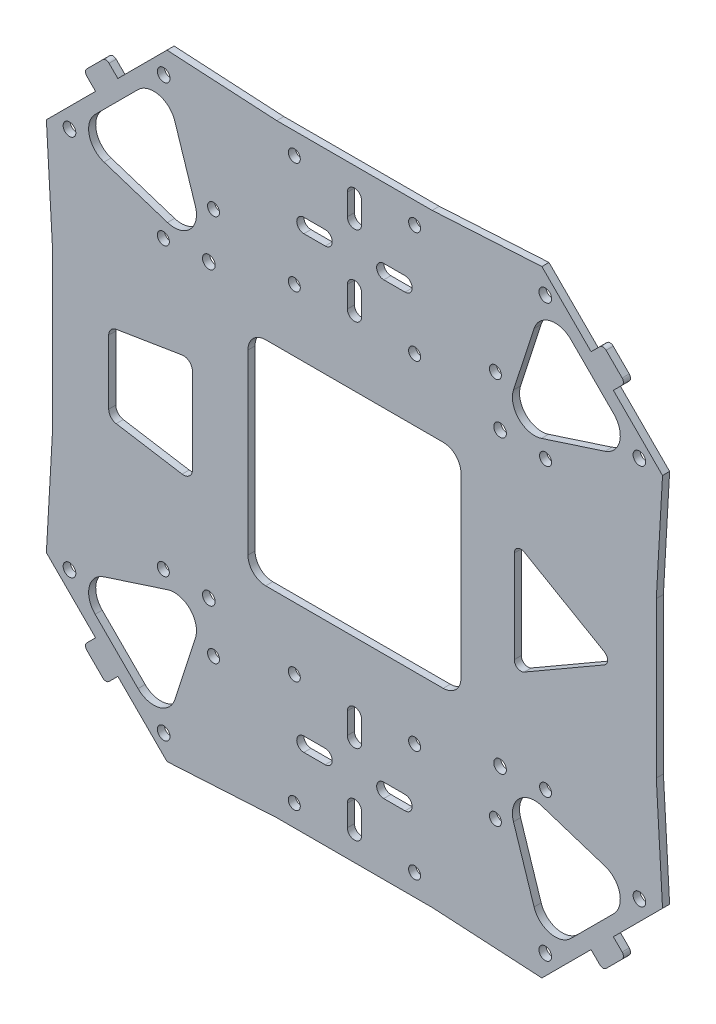
SolidWorks part; units mm, degrees
ref_plane "Front Plane" through (0, 0, 0) normal (0, 0, 1) x (1, 0, 0)
ref_plane "Top Plane" through (0, 0, 0) normal (0, 1, 0) x (1, 0, 0)
ref_plane "Right Plane" through (0, 0, 0) normal (1, 0, 0) x (0, 0, -1)
sketch "Sketch1" plane through (0, 0, 0) normal (0, 0, 1) x (1, 0, 0)
  line L16 (68, 0) -> (68, 17.5)
  line L17 (68, 0) -> (68, -17.5)
  line L21 (68, 17.5) -> (69.4, 42.225)
  line L23 (68, -17.5) -> (69.4, -42.225)
  line L24 (-68, 0) -> (-68, 17.5)
  line L25 (-68, 0) -> (-68, -17.5)
  line L30 (-68, 17.5) -> (-69.4, 42.225)
  line L31 (-68, -17.5) -> (-69.4, -42.225)
  line L32 (0, -68) -> (-17.5, -68)
  line L33 (0, -68) -> (17.5, -68)
  line L37 (42.225, -68) -> (42.225, -69.4) construction
  line L38 (-17.5, -68) -> (-42.225, -69.4)
  line L39 (17.5, -68) -> (42.225, -69.4)
  line L40 (0, 68) -> (-17.5, 68)
  line L41 (0, 68) -> (17.5, 68)
  line L46 (-17.5, 68) -> (-42.225, 69.4)
  line L47 (17.5, 68) -> (42.225, 69.4)
  line L48 (-69.4, 42.225) -> (-58.3227, 53.3023)
  line L49 (-53.3023, 58.3227) -> (-42.225, 69.4)
  line L50 (-58.4995, 58.4995) -> (-61.0097, 55.9893)
  line L51 (-58.4995, 58.4995) -> (-55.9893, 61.0097)
  line L52 (-61.0097, 55.9893) -> (-58.3227, 53.3023)
  line L53 (-55.9893, 61.0097) -> (-53.3023, 58.3227)
  line L54 (42.225, 69.4) -> (53.3023, 58.3227)
  line L55 (-69.4, -42.225) -> (-58.3227, -53.3023)
  line L56 (42.225, -69.4) -> (53.3023, -58.3227)
  line L57 (58.3227, -53.3023) -> (69.4, -42.225)
  line L58 (58.4995, 58.4995) -> (55.9893, 61.0097)
  line L59 (58.4995, 58.4995) -> (61.0097, 55.9893)
  line L60 (55.9893, 61.0097) -> (53.3023, 58.3227)
  line L61 (61.0097, 55.9893) -> (58.3227, 53.3023)
  line L64 (58.4995, -58.4995) -> (55.9893, -61.0097)
  line L65 (58.4995, -58.4995) -> (61.0097, -55.9893)
  line L66 (55.9893, -61.0097) -> (53.3023, -58.3227)
  line L67 (61.0097, -55.9893) -> (58.3227, -53.3023)
  line L68 (-53.3023, -58.3227) -> (-42.225, -69.4)
  line L69 (-58.4995, -58.4995) -> (-61.0097, -55.9893)
  line L70 (-58.4995, -58.4995) -> (-55.9893, -61.0097)
  line L71 (-61.0097, -55.9893) -> (-58.3227, -53.3023)
  line L72 (-55.9893, -61.0097) -> (-53.3023, -58.3227)
  line L75 (58.3227, 53.3023) -> (69.4, 42.225)
  point P0 (0, 0)
  point P6 (0, 0)
  dimension "D3" = 3.8
  dimension "D9" = 17.5
  dimension "D10" = 17.5
  dimension "D13" = 17.5
  dimension "D14" = 17.5
  dimension "D16" = 24.725
  dimension "D18" = 3.55
  dimension "D19" = 3.55
  dimension "D21" = 3.55
  dimension "D22" = 3.55
  dimension "D24" = 3.55
extrude "Boss-Extrude1" add sketch "Sketch1" along normal blind 1.6
ref_plane "Plane1" through (0, 0, 1.6) normal (0, 0, 1) x (1, 0, 0)
sketch "Sketch2" plane through (0, 0, 1.6) normal (0, 0, 1) x (1, 0, 0)
  line L0 (24, 0) -> (36, 0) construction
  line L1 (20, -24) -> (-20, -24)
  line L2 (24, -20) -> (24, 20)
  line L3 (20, 24) -> (-20, 24)
  line L4 (-24, -20) -> (-24, 20)
  line L5 (24, -24) -> (-24, 24) construction
  line L6 (24, 24) -> (-24, -24) construction
  line L7 (36, 0) -> (36, 10.4019)
  line L8 (36, 0) -> (36, -10.4019)
  line L9 (36, 0) -> (58.5167, 0) construction
  line L10 (38.25, 11.701) -> (56.2667, 1.299)
  line L11 (38.25, -11.701) -> (56.2667, -1.299)
  line L12 (-24, 0) -> (-36.5, 0) construction
  line L13 (-36.5, 0) -> (-36.5, 9.6475)
  line L14 (-36.5, 0) -> (-36.5, -9.6475)
  line L15 (-36.5, 0) -> (-55.36, 0) construction
  line L16 (-55.36, 0) -> (-55.36, 7.2247)
  line L17 (-55.36, 0) -> (-55.36, -7.2247)
  line L18 (-53.6818, 9.1986) -> (-38.8218, 11.6214)
  line L19 (-53.6818, -9.1986) -> (-38.8218, -11.6214)
  line L20 (0, 0) -> (0, 32.15) construction
  line L21 (0, 0) -> (0, -32.15) construction
  line L22 (0, 0) -> (-31.65, 0) construction
  line L23 (0, 0) -> (-31.65, 0) construction
  line L24 (-31.65, 0) -> (-31.65, 32.15) construction
  line L25 (-31.65, 0) -> (-31.65, -32.15) construction
  line L26 (0, 0) -> (31.65, 0) construction
  line L27 (31.65, 0) -> (31.65, 32.15) construction
  line L28 (31.65, 0) -> (31.65, -32.15) construction
  arc A0 (20, -24) -> (24, -20) centre (20, -20) ccw
  arc A1 (24, 20) -> (20, 24) centre (20, 20) ccw
  arc A2 (-20, -24) -> (-24, -20) centre (-20, -20) cw
  arc A3 (-24, 20) -> (-20, 24) centre (-20, 20) cw
  arc A4 (38.25, -11.701) -> (36, -10.4019) centre (37.5, -10.4019) cw
  arc A5 (36, 10.4019) -> (38.25, 11.701) centre (37.5, 10.4019) cw
  arc A6 (56.2667, -1.299) -> (56.2667, 1.299) centre (55.5167, 0) ccw
  arc A7 (-53.6818, -9.1986) -> (-55.36, -7.2247) centre (-53.36, -7.2247) cw
  arc A8 (-38.8218, -11.6214) -> (-36.5, -9.6475) centre (-38.5, -9.6475) ccw
  arc A9 (-36.5, 9.6475) -> (-38.8218, 11.6214) centre (-38.5, 9.6475) ccw
  arc A10 (-55.36, 7.2247) -> (-53.6818, 9.1986) centre (-53.36, 7.2247) cw
  point P0 (0, 0)
  point P25 (36, -13)
  point P28 (36, 13)
  point P41 (-55.36, -8.925)
  point P44 (-36.5, -12)
  point P47 (-36.5, 12)
  point P50 (-55.36, 8.925)
  dimension "D3" = 4
  dimension "D8" = 1.5
  dimension "D15" = 2
  dimension "D1" = 48
  dimension "D2" = 48
  dimension "D4" = 12
  dimension "D5" = 13
  dimension "D6" = 13
  dimension "D7" = 26
  dimension "D9" = 12.5
  dimension "D10" = 12
  dimension "D11" = 12
  dimension "D12" = 18.86
  dimension "D13" = 8.925
  dimension "D14" = 8.925
  dimension "D16" = 32.15
  dimension "D17" = 32.15
  dimension "D18" = 31.65
  dimension "D19" = 31.65
extrude "Cut-Extrude1" cut sketch "Sketch2" against normal through all
ref_plane "Plane2" through (0, 0, 1.6) normal (0, 0, 1) x (1, 0, 0)
sketch "Sketch3" plane through (0, 0, 1.6) normal (0, 0, 1) x (1, 0, 0)
  line L0 (0, 0) -> (-43.05, 0) construction
  line L1 (0, 0) -> (43.05, 0) construction
  line L3 (-43.05, 0) -> (-43.05, 32.275) construction
  line L4 (-43.05, 0) -> (-43.05, -32.275) construction
  line L5 (43.05, 0) -> (43.05, 32.275) construction
  line L6 (43.05, 0) -> (43.05, -32.275) construction
  circle A0 centre (-43.05, -32.275) radius 1.35
  circle A1 centre (-43.05, 32.275) radius 1.35
  circle A2 centre (43.05, 32.275) radius 1.35
  circle A3 centre (43.05, -32.275) radius 1.35
  dimension "D5" = 2.7
  dimension "D6" = 2.7
  dimension "D7" = 2.7
  dimension "D8" = 2.7
  dimension "D1" = 43.05
  dimension "D2" = 43.05
  dimension "D3" = 32.275
  dimension "D4" = 32.275
extrude "Cut-Extrude2" cut sketch "Sketch3" against normal blind 10
ref_plane "Plane3" through (0, 0, 1.6) normal (0, 0, 1) x (1, 0, 0)
sketch "Sketch4" plane through (0, 0, 1.6) normal (0, 0, 1) x (1, 0, 0)
  line L0 (0, 0) -> (31.75, 0) construction
  line L1 (0, 0) -> (-31.75, 0) construction
  line L2 (-31.75, 0) -> (-31.75, 42.25) construction
  line L3 (-31.75, 0) -> (-31.75, -42.25) construction
  line L4 (31.75, 0) -> (31.75, 43.6) construction
  line L5 (31.75, 0) -> (31.75, -43.6) construction
  line L6 (0, 0) -> (0, 38.05) construction
  line L7 (0, 0) -> (0, -38.05) construction
  line L8 (-13.55, -63.15) -> (13.55, -38.05) construction
  line L9 (0, -50.6) -> (0, -55.6) construction
  line L10 (0, -38.05) -> (13.55, -38.05) construction
  line L11 (0, -38.05) -> (-13.55, -38.05) construction
  line L12 (-6.6, -52.2) -> (-11.4, -52.2)
  line L13 (-1.6, -57.2) -> (-1.6, -62)
  line L14 (-13.55, -38.05) -> (-13.55, -63.15) construction
  line L15 (13.55, -38.05) -> (13.55, -63.15) construction
  line L16 (1.6, -57.2) -> (1.6, -62)
  line L17 (-6.6, -49) -> (-11.4, -49)
  line L18 (-1.6, -44) -> (-1.6, -39.2)
  line L39 (1.6, -44) -> (1.6, -39.2)
  line L40 (6.6, -49) -> (11.4, -49)
  line L41 (6.6, -52.2) -> (11.4, -52.2)
  line L42 (0, 38.05) -> (-13.55, 38.05) construction
  line L43 (0, 38.05) -> (13.55, 38.05) construction
  line L44 (-13.55, 38.05) -> (-13.55, 63.15) construction
  line L45 (13.55, 38.05) -> (13.55, 63.15) construction
  line L46 (-13.55, 63.15) -> (13.55, 63.15) construction
  line L47 (13.55, 63.15) -> (-13.55, 38.05) construction
  line L48 (0, 50.6) -> (0, 55.6) construction
  line L49 (6.6, 49) -> (11.4, 49)
  line L50 (-1.6, 57.2) -> (-1.6, 62)
  line L51 (1.6, 57.2) -> (1.6, 62)
  line L52 (6.6, 52.2) -> (11.4, 52.2)
  line L53 (-1.6, 44) -> (-1.6, 39.2)
  line L54 (1.6, 44) -> (1.6, 39.2)
  line L55 (-6.6, 52.2) -> (-11.4, 52.2)
  line L56 (-6.6, 49) -> (-11.4, 49)
  circle A0 centre (-31.75, -43.6) radius 1.35
  circle A1 centre (31.75, -43.6) radius 1.35
  circle A2 centre (31.75, 43.6) radius 1.35
  circle A3 centre (-31.75, 43.6) radius 1.35
  circle A4 centre (13.55, -38.05) radius 1.35
  circle A5 centre (-13.55, -38.05) radius 1.35
  circle A6 centre (13.55, 38.05) radius 1.35
  circle A7 centre (-13.55, 38.05) radius 1.35
  circle A8 centre (-13.55, 63.15) radius 1.35
  circle A10 centre (-13.55, -63.15) radius 1.35
  circle A11 centre (13.55, -63.15) radius 1.35
  arc A21 (1.6, -57.2) -> (-1.6, -57.2) centre (0, -57.2) ccw
  arc A22 (-1.6, -62) -> (1.6, -62) centre (0, -62) ccw
  arc A23 (-6.6, -52.2) -> (-6.6, -49) centre (-6.6, -50.6) ccw
  arc A24 (-11.4, -49) -> (-11.4, -52.2) centre (-11.4, -50.6) ccw
  arc A25 (-1.6, -44) -> (1.6, -44) centre (0, -44) ccw
  arc A26 (1.6, -39.2) -> (-1.6, -39.2) centre (0, -39.2) ccw
  arc A27 (6.6, -49) -> (6.6, -52.2) centre (6.6, -50.6) ccw
  arc A28 (11.4, -52.2) -> (11.4, -49) centre (11.4, -50.6) ccw
  circle A29 centre (13.55, 63.15) radius 1.35
  arc A30 (-1.6, 57.2) -> (1.6, 57.2) centre (0, 57.2) ccw
  arc A31 (1.6, 62) -> (-1.6, 62) centre (0, 62) ccw
  arc A32 (11.4, 49) -> (11.4, 52.2) centre (11.4, 50.6) ccw
  arc A33 (6.6, 52.2) -> (6.6, 49) centre (6.6, 50.6) ccw
  arc A34 (-1.6, 39.2) -> (1.6, 39.2) centre (0, 39.2) ccw
  arc A35 (1.6, 44) -> (-1.6, 44) centre (0, 44) ccw
  arc A36 (-11.4, 52.2) -> (-11.4, 49) centre (-11.4, 50.6) ccw
  arc A37 (-6.6, 49) -> (-6.6, 52.2) centre (-6.6, 50.6) ccw
  point P64 (0, 50.6)
  point P87 (0, -50.6)
  point P89 (0, 50.6)
  dimension "D5" = 2.7
  dimension "D6" = 2.7
  dimension "D7" = 2.7
  dimension "D8" = 2.7
  dimension "D13" = 2.7
  dimension "D14" = 2.7
  dimension "D15" = 2.7
  dimension "D16" = 2.7
  dimension "D19" = 2.7
  dimension "D20" = 2.7
  dimension "D21" = 2.7
  dimension "D22" = 2.7
  dimension "D1" = 31.75
  dimension "D2" = 31.75
  dimension "D3" = 43.6
  dimension "D4" = 43.6
  dimension "D9" = 5
  dimension "D10" = 38.05
  dimension "D11" = 1.6
  dimension "D12" = 4.8
  dimension "D17" = 25.1
  dimension "D18" = 25.1
  dimension "D23" = 4
  dimension "D24" = 38.05
  dimension "D25" = 13.55
  dimension "D26" = 13.55
  dimension "D27" = 5
  dimension "D28" = 1.6
  dimension "D29" = 4.8
  dimension "D30" = 4
extrude "Cut-Extrude3" cut sketch "Sketch4" against normal blind 10
ref_plane "Plane4" through (0, 0, 1.6) normal (0, 0, 1) x (1, 0, 0)
fillet "Fillet1" radius 1 2 edges at (-61.0097, 55.9893, 0.8) (-55.9893, 61.0097, 0.8)
fillet "Fillet2" radius 1 6 edges at (-61.0097, -55.9893, 0.8) (-55.9893, -61.0097, 0.8) (61.0097, -55.9893, 0.8) (55.9893, -61.0097, 0.8) (61.0097, 55.9893, 0.8) (55.9893, 61.0097, 0.8)
ref_plane "Plane5" through (0, 0, 1.6) normal (0, 0, 1) x (1, 0, 0)
sketch "Sketch5" plane through (0, 0, 1.6) normal (0, 0, 1) x (1, 0, 0)
  line L0 (-53.3023, 58.3227) -> (-58.3227, 53.3023) construction
  line L1 (-55.8125, 55.8125) -> (-66.4191, 45.2059) construction
  line L2 (-58.3227, 53.3023) -> (-69.4, 42.225) construction
  line L3 (-55.8125, 55.8125) -> (-45.2059, 66.4191) construction
  line L4 (-42.225, 69.4) -> (-53.3023, 58.3227) construction
  line L5 (-66.4191, 45.2059) -> (-64.1951, 42.9819) construction
  line L6 (-45.2059, 66.4191) -> (-42.9819, 64.1951) construction
  line L7 (-64.1951, 42.9819) -> (-42.9819, 64.1951) construction
  line L8 (-64.1951, 42.9819) -> (-32.8038, 32.8041) construction
  line L9 (-32.8038, 32.8041) -> (-42.9819, 64.1951) construction
  line L10 (-35.8258, 42.1243) -> (-40.4636, 56.4282)
  line L11 (-48.7554, 58.4216) -> (-58.4216, 48.7554)
  line L12 (-56.4281, 40.4637) -> (-42.1241, 35.8259)
  line L13 (40.4637, 56.4281) -> (35.8259, 42.1241)
  line L14 (42.1243, 35.8258) -> (56.4282, 40.4636)
  line L15 (58.4216, 48.7554) -> (48.7554, 58.4216)
  line L16 (56.4281, -40.4637) -> (42.1241, -35.8259)
  line L17 (35.8258, -42.1243) -> (40.4636, -56.4282)
  line L18 (48.7554, -58.4216) -> (58.4216, -48.7554)
  line L19 (-40.4637, -56.4281) -> (-35.8259, -42.1241)
  line L20 (-42.1243, -35.8258) -> (-56.4282, -40.4636)
  line L21 (-58.4216, -48.7554) -> (-48.7554, -58.4216)
  circle A0 centre (-64.1951, 42.9819) radius 1.425
  circle A1 centre (-42.9819, 64.1951) radius 1.425
  circle A2 centre (-32.8038, 32.8041) radius 1.425
  arc A3 (-42.1241, 35.8259) -> (-35.8258, 42.1243) centre (-40.582, 40.5822) ccw
  arc A4 (-40.4636, 56.4282) -> (-48.7554, 58.4216) centre (-45.2198, 54.8861) ccw
  arc A5 (-58.4216, 48.7554) -> (-56.4281, 40.4637) centre (-54.886, 45.2199) ccw
  arc A6 (48.7554, 58.4216) -> (40.4637, 56.4281) centre (45.2199, 54.886) ccw
  arc A7 (35.8259, 42.1241) -> (42.1243, 35.8258) centre (40.5822, 40.582) ccw
  arc A8 (56.4282, 40.4636) -> (58.4216, 48.7554) centre (54.8861, 45.2198) ccw
  circle A9 centre (42.9819, 64.1951) radius 1.425
  circle A10 centre (64.1951, 42.9819) radius 1.425
  circle A11 centre (32.8041, 32.8038) radius 1.425
  arc A12 (58.4216, -48.7554) -> (56.4281, -40.4637) centre (54.886, -45.2199) ccw
  arc A13 (42.1241, -35.8259) -> (35.8258, -42.1243) centre (40.582, -40.5822) ccw
  arc A14 (40.4636, -56.4282) -> (48.7554, -58.4216) centre (45.2198, -54.8861) ccw
  circle A15 centre (64.1951, -42.9819) radius 1.425
  circle A16 centre (42.9819, -64.1951) radius 1.425
  circle A17 centre (32.8038, -32.8041) radius 1.425
  arc A18 (-48.7554, -58.4216) -> (-40.4637, -56.4281) centre (-45.2199, -54.886) ccw
  arc A19 (-35.8259, -42.1241) -> (-42.1243, -35.8258) centre (-40.5822, -40.582) ccw
  arc A20 (-56.4282, -40.4636) -> (-58.4216, -48.7554) centre (-54.8861, -45.2198) ccw
  circle A21 centre (-42.9819, -64.1951) radius 1.425
  circle A22 centre (-64.1951, -42.9819) radius 1.425
  circle A23 centre (-32.8041, -32.8038) radius 1.425
  point P74 (0, 0)
  dimension "D5" = 2.85
  dimension "D6" = 2.85
  dimension "D9" = 2.85
  dimension "D10" = 5
  dimension "D1" = 15
  dimension "D2" = 15
  dimension "D3" = 3.1452
  dimension "D4" = 3.1452
  dimension "D7" = 62.964
  dimension "D8" = 33
  dimension "D11" = 4
extrude "Cut-Extrude4" cut sketch "Sketch5" against normal blind 10
ref_plane "Plane6" through (0, 0, 101.6) normal (0, 0, 1) x (1, 0, 0)
